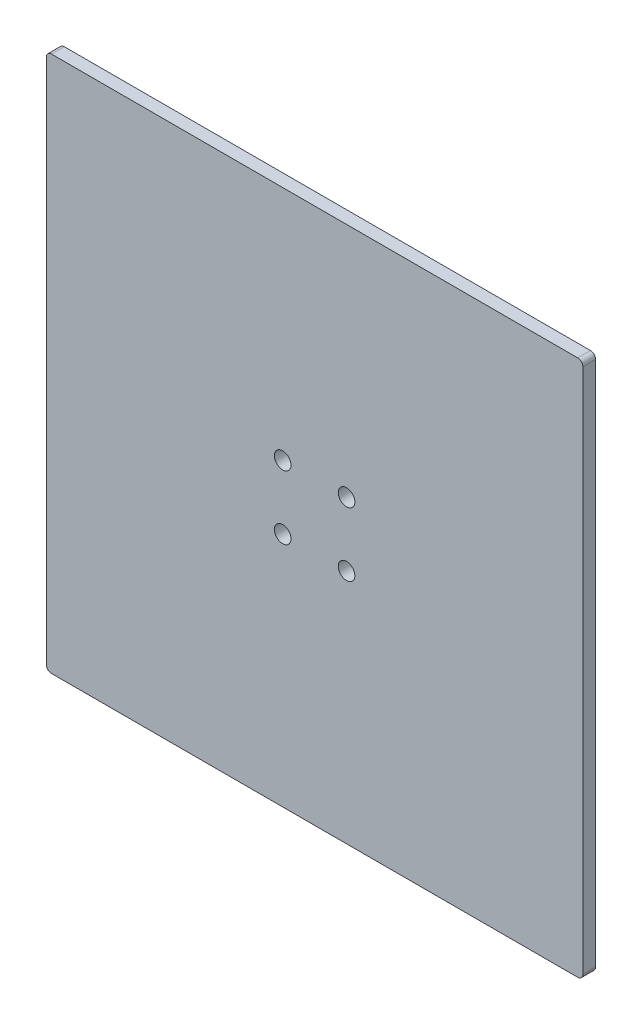
SolidWorks part; units mm, degrees
ref_plane "Alzado" through (0, 0, 0) normal (0, 0, 1) x (1, 0, 0)
ref_plane "Planta" through (0, 0, 0) normal (0, 1, 0) x (1, 0, 0)
ref_plane "Vista lateral" through (0, 0, 0) normal (1, 0, 0) x (0, 0, -1)
sketch "Croquis1" plane through (0, 0, 0) normal (0, 0, 1) x (1, 0, 0)
  line L0 (-12.5, -12.5) -> (-105, -105) construction
  line L1 (105, 105) -> (-105, 105)
  line L2 (105, 105) -> (105, -105)
  line L3 (105, -105) -> (-105, -105)
  line L4 (-105, 105) -> (-105, -105)
  line L5 (105, 105) -> (12.5, 12.5) construction
  line L6 (105, -105) -> (12.5, -12.5) construction
  line L11 (10.2019, 10.2019) -> (-10.2019, -10.2019) construction
  line L12 (10.2019, -10.2019) -> (-10.2019, 10.2019) construction
  line L13 (-12.5, 12.5) -> (-105, 105) construction
  line L14 (10.2019, -10.2019) -> (-10.2019, 10.2019) construction
  line L15 (10.2019, 10.2019) -> (-10.2019, -10.2019) construction
  line L16 (12.5, -12.5) -> (-12.5, -12.5) construction
  line L17 (12.5, -12.5) -> (12.5, 12.5) construction
  circle A0 centre (-12.5, 12.5) radius 3.25
  circle A1 centre (12.5, 12.5) radius 3.25
  circle A2 centre (-12.5, -12.5) radius 3.25
  circle A3 centre (12.5, -12.5) radius 3.25
  point P0 (0, 0)
  point P6 (0, 0)
  point P15 (0, 0)
  point P18 (0, 0)
  point P21 (0, 0)
  dimension "D5" = 6.5
  dimension "D6" = 6.5
  dimension "D7" = 6.5
  dimension "D8" = 6.5
  dimension "D1" = 210
  dimension "D2" = 210
  dimension "D3" = 25
extrude "Saliente-Extruir1" add sketch "Croquis1" along normal blind 5
fillet "Redondeo1" radius 2 4 edges at (105, -105, 2.5) (-105, -105, 2.5) (105, 105, 2.5) (-105, 105, 2.5)
